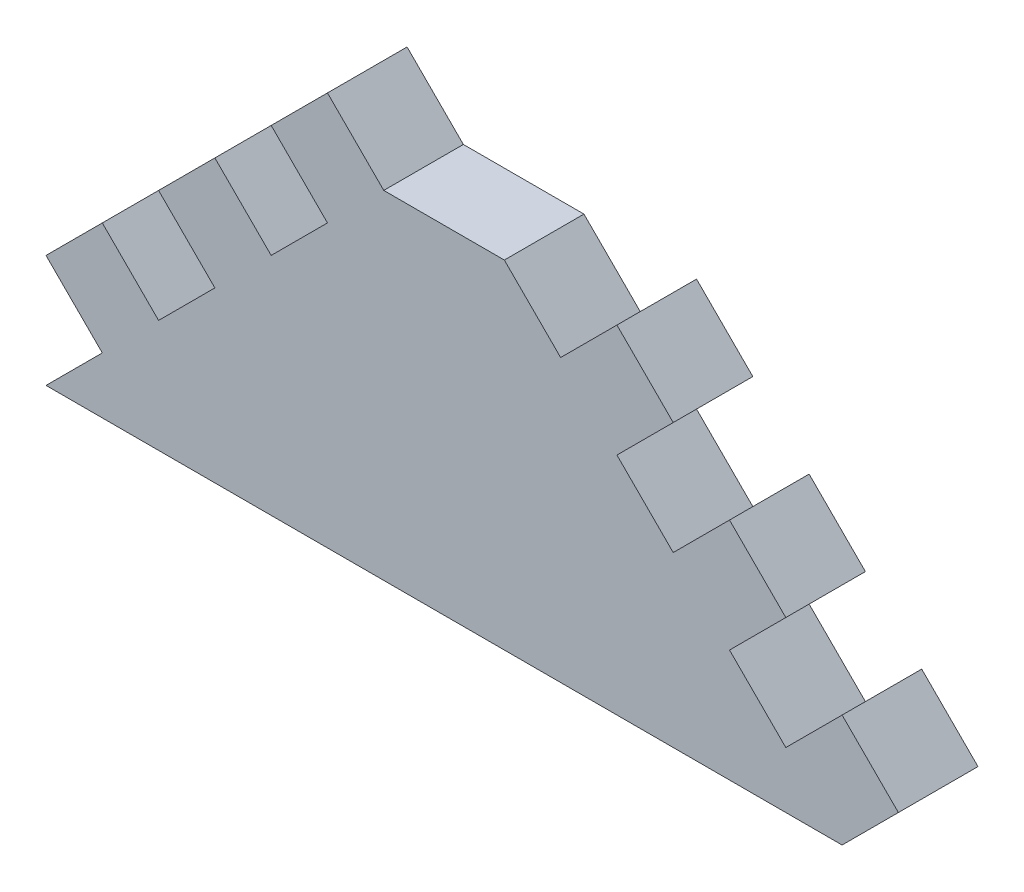
SolidWorks part; units mm, degrees
ref_plane "Спереди" through (0, 0, 0) normal (0, 0, 1) x (1, 0, 0)
ref_plane "Сверху" through (0, 0, 0) normal (0, 1, 0) x (1, 0, 0)
ref_plane "Справа" through (0, 0, 0) normal (1, 0, 0) x (0, 0, -1)
sketch "Эскиз1" plane through (0, 0, 0) normal (0, 0, 1) x (1, 0, 0)
  line L0 (0, 0) -> (50, 0)
  line L1 (28.7868, 21.2132) -> (32.3223, 17.6777)
  line L2 (28.7868, 21.2132) -> (21.2132, 21.2132)
  line L3 (0, 0) -> (3.5355, 3.5355)
  line L4 (3.5355, 3.5355) -> (0, 7.0711)
  line L5 (0, 7.0711) -> (3.5355, 10.6066)
  line L6 (3.5355, 10.6066) -> (7.0711, 7.0711)
  line L7 (7.0711, 7.0711) -> (10.6066, 10.6066)
  line L8 (10.6066, 10.6066) -> (7.0711, 14.1421)
  line L9 (7.0711, 14.1421) -> (10.6066, 17.6777)
  line L10 (10.6066, 17.6777) -> (14.1421, 14.1421)
  line L11 (14.1421, 14.1421) -> (17.6777, 17.6777)
  line L12 (17.6777, 17.6777) -> (14.1421, 21.2132)
  line L13 (14.1421, 21.2132) -> (17.6777, 24.7487)
  line L14 (17.6777, 24.7487) -> (21.2132, 21.2132)
  line L15 (32.3223, 17.6777) -> (35.8579, 21.2132)
  line L16 (35.8579, 21.2132) -> (39.3934, 17.6777)
  line L17 (39.3934, 17.6777) -> (35.8579, 14.1421)
  line L18 (35.8579, 14.1421) -> (39.3934, 10.6066)
  line L19 (39.3934, 10.6066) -> (42.9289, 14.1421)
  line L20 (42.9289, 14.1421) -> (46.4645, 10.6066)
  line L21 (46.4645, 10.6066) -> (42.9289, 7.0711)
  line L22 (42.9289, 7.0711) -> (46.4645, 3.5355)
  line L23 (46.4645, 3.5355) -> (50, 7.0711)
  line L24 (50, 7.0711) -> (53.5355, 3.5355)
  line L25 (53.5355, 3.5355) -> (50, 0)
  point P5 (47.4272, 20.5228)
  point P6 (51.5514, 6.8988)
  point P29 (53.0039, 6.3807)
  dimension "D1" = 5
  dimension "D2" = 50
  dimension "D3" = 45
extrude "Бобышка-Вытянуть1" add sketch "Эскиз1" along normal blind 5
sketch "Эскиз2" plane through (7.3223, -7.3223, 0) normal (-0.7071, 0.7071, 0) x (0.7071, 0.7071, 0)
  line L0 (40.3553, 0) -> (35.3553, 0) construction
  line L2 (52.1405, -5) -> (52.1405, 0)
  line L3 (52.1405, 0) -> (35.3553, 0)
  line L5 (52.1405, -5) -> (35.3553, 0) construction
  line L7 (35.3553, -5) -> (35.3553, 0) construction
  point P0 (48.9412, -4.047)
  dimension "D1" = 5
